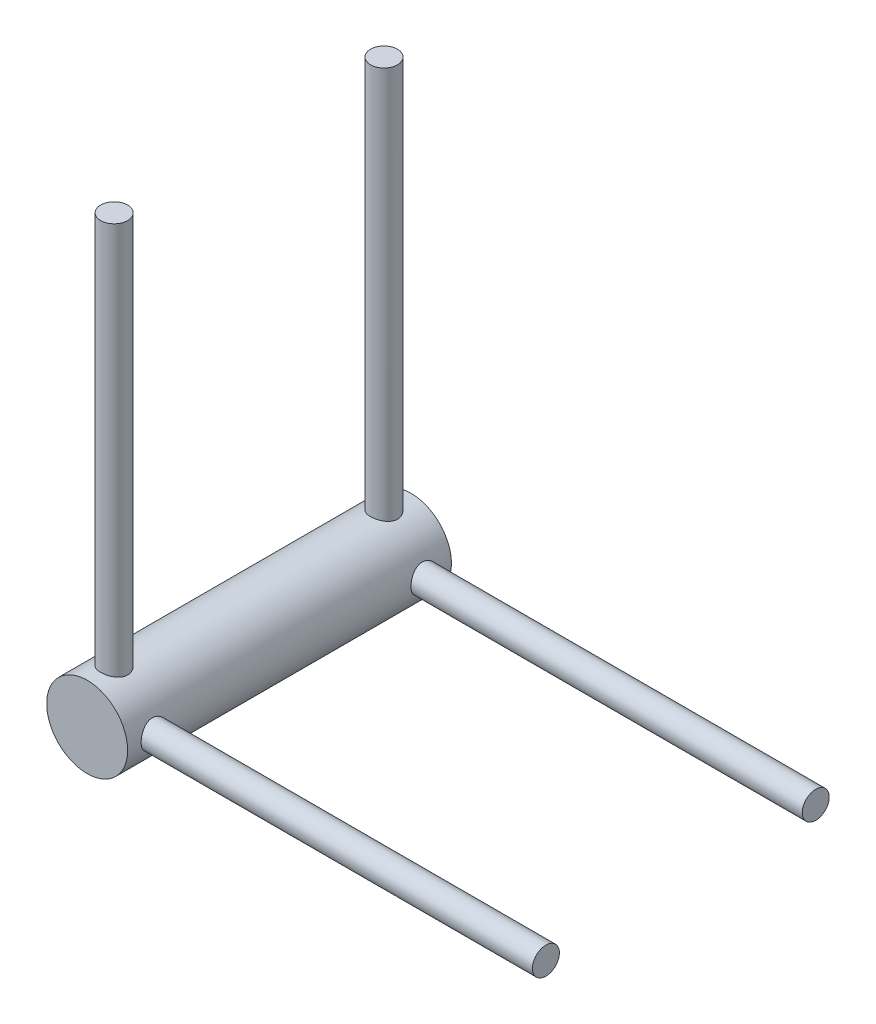
SolidWorks part; units mm, degrees
ref_plane "Front Plane" through (0, 0, 0) normal (0, 0, 1) x (1, 0, 0)
ref_plane "Top Plane" through (0, 0, 0) normal (0, 1, 0) x (1, 0, 0)
ref_plane "Right Plane" through (0, 0, 0) normal (1, 0, 0) x (0, 0, -1)
sketch "Sketch1" plane through (0, 0, 0) normal (0, 0, 1) x (1, 0, 0)
  circle A0 centre (0, 0) radius 9.525
  dimension "D1" = 19.05
extrude "Boss-Extrude1" add sketch "Sketch1" along normal mid plane 76.2
sketch "Sketch2" plane through (0, 0, 0) normal (1, 0, 0) x (0, 0, -1)
  line L0 (-31.75, 0) -> (31.75, 0) construction
  circle A0 centre (-31.75, 0) radius 3.175
  circle A1 centre (31.75, 0) radius 3.175
  point P4 (0, 0)
  dimension "D2" = 6.35
  dimension "D1" = 63.5
extrude "Boss-Extrude2" add sketch "Sketch2" along normal blind 101.6
sketch "Sketch3" plane through (0, 0, 0) normal (0, 1, 0) x (1, 0, 0)
  line L0 (0, -31.75) -> (0, 31.75) construction
  circle A0 centre (0, 31.75) radius 3.175
  circle A1 centre (0, -31.75) radius 3.175
  point P4 (0, 0)
  dimension "D2" = 6.35
  dimension "D1" = 63.5
extrude "Boss-Extrude3" add sketch "Sketch3" along normal blind 101.6
